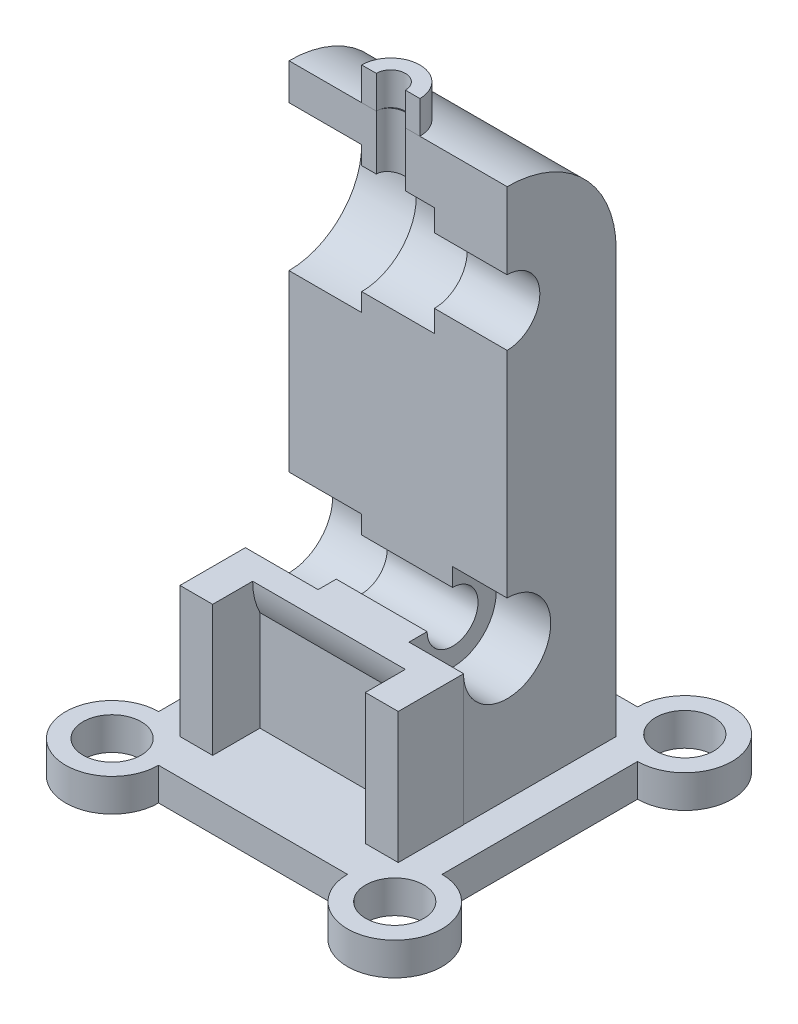
SolidWorks part; units mm, degrees
ref_plane "Ön Düzlem" through (0, 0, 0) normal (0, 0, 1) x (1, 0, 0)
ref_plane "Üst Düzlem" through (0, 0, 0) normal (0, 1, 0) x (1, 0, 0)
ref_plane "Sağ Düzlem" through (0, 0, 0) normal (1, 0, 0) x (0, 0, -1)
sketch "Sketch1" plane through (0, 0, 0) normal (0, 1, 0) x (1, 0, 0)
  line L1 (-62.3416, 5.3221) -> (-10.5841, 5.3221)
  line L2 (-75.3416, -7.6779) -> (-75.3416, -61.6779)
  line L3 (-62.5552, -74.4643) -> (-10.5841, -74.4643)
  line L4 (2.4159, -7.6779) -> (2.4159, -61.4643)
  circle A0 centre (2.4159, 5.3221) radius 8
  circle A1 centre (-75.3416, 5.3221) radius 8
  arc A2 (-62.3416, 5.3221) -> (-75.3416, -7.6779) centre (-75.3416, 5.3221) ccw
  arc A3 (2.4159, -7.6779) -> (-10.5841, 5.3221) centre (2.4159, 5.3221) ccw
  circle A4 centre (-75.3416, -74.4643) radius 8
  arc A5 (-75.3416, -61.6779) -> (-62.5552, -74.4643) centre (-75.3416, -74.4643) ccw
  circle A6 centre (2.4159, -74.4643) radius 8
  arc A7 (-10.5841, -74.4643) -> (2.4159, -61.4643) centre (2.4159, -74.4643) ccw
extrude "Boss-Extrude1" add sketch "Sketch1" along normal blind 9
sketch "Sketch2" plane through (0, 9, 0) normal (0, 1, 0) x (1, 0, 0)
  line L0 (-66.4629, -64.6779) -> (-57.4629, -64.6779)
  line L1 (-66.4629, -4.6779) -> (-6.4629, -4.6779)
  line L2 (-66.4629, -4.6779) -> (-66.4629, -64.6779)
  line L3 (-66.4629, -64.6779) -> (-57.4629, -64.6779)
  line L4 (-6.4629, -4.6779) -> (-6.4629, -64.6779)
  line L5 (-66.4629, -4.6779) -> (-6.4629, -64.6779) construction
  line L6 (-66.4629, -64.6779) -> (-6.4629, -4.6779) construction
  line L8 (-15.4629, -64.6779) -> (-15.4629, -53.6779)
  line L9 (-15.4629, -53.6779) -> (-57.4629, -53.6779)
  line L10 (-57.4629, -53.6779) -> (-57.4629, -64.6779)
  line L11 (-66.4629, -64.6779) -> (-66.4629, -46.6779)
  line L12 (-66.4629, -46.6779) -> (-46.4629, -46.6779)
  line L13 (-46.4629, -46.6779) -> (-46.4629, -41.6779)
  line L14 (-46.4629, -41.6779) -> (-21.4629, -41.6779)
  line L15 (-21.4629, -41.6779) -> (-21.4629, -46.6779)
  line L16 (-21.4629, -46.6779) -> (-6.4629, -46.6779)
  line L17 (-15.4629, -64.6779) -> (-6.4629, -64.6779)
  point P0 (-36.4629, -34.6779)
extrude "Boss-Extrude2" add sketch "Sketch2" along normal blind 36 contours L15 L16 L4 L1 L2 L12 L13 L14
sketch "Sketch3" plane through (-66.4629, 0, 0) normal (-1, 0, 0) x (0, 0, 1)
  line L1 (4.6779, 45) -> (46.6779, 45) construction
  line L2 (34.6779, 45) -> (34.6779, 125)
  line L3 (34.6779, 125) -> (4.6779, 125)
  line L4 (4.6779, 125) -> (4.6779, 45)
  line L5 (4.6779, 45) -> (34.6779, 45)
extrude "Boss-Extrude3" add sketch "Sketch3" against normal blind 60
sketch "Sketch4" plane through (-66.4629, 0, 0) normal (-1, 0, 0) x (0, 0, 1)
  circle A0 centre (34.6779, 45) radius 12
extrude "Cut-Extrude2" cut sketch "Sketch4" against normal blind 20
sketch "Sketch5" plane through (-46.4629, 0, 0) normal (-1, 0, 0) x (0, 0, 1)
  circle A0 centre (34.6779, 45) radius 7
extrude "Cut-Extrude3" cut sketch "Sketch5" against normal blind 25
sketch "Sketch6" plane through (-6.4629, 0, 0) normal (1, 0, 0) x (0, 0, -1)
  circle A0 centre (-34.6779, 45) radius 12
extrude "Cut-Extrude4" cut sketch "Sketch6" against normal blind 15
sketch "Sketch7" plane through (0, 9, 0) normal (0, 1, 0) x (1, 0, 0)
  line L0 (-66.4629, -64.6779) -> (-57.4629, -64.6779)
  line L2 (-66.4629, -46.6779) -> (-66.4629, -64.6779)
  line L3 (-66.4629, -64.6779) -> (-57.4629, -64.6779)
  line L4 (-6.413, -46.6779) -> (-6.413, -64.6779)
  line L5 (-57.4629, -64.6779) -> (-57.4629, -51.6779)
  line L6 (-57.4629, -51.6779) -> (-15.4629, -51.6779)
  line L7 (-15.4629, -51.6779) -> (-15.4629, -64.6779)
  line L8 (-15.4629, -64.6779) -> (-6.413, -64.6779)
  line L9 (-6.413, -46.6779) -> (-21.4629, -46.6779)
  line L10 (-21.4629, -46.6779) -> (-21.4629, -41.6779)
  line L11 (-21.4629, -41.6779) -> (-46.4629, -41.6779)
  line L12 (-46.4629, -41.6779) -> (-46.4629, -46.6779)
  line L13 (-46.4629, -46.6779) -> (-66.4629, -46.6779)
extrude "Boss-Extrude4" add sketch "Sketch7" along normal blind 36
sketch "Sketch9" plane through (-66.4629, 0, 0) normal (-1, 0, 0) x (0, 0, 1)
  line L0 (53.6779, 45) -> (46.6779, 45)
  line L1 (22.6779, 45) -> (15.6779, 45)
  circle A0 centre (34.6779, 125) radius 20
  arc A1 (15.6779, 45) -> (53.6779, 45) centre (34.6779, 45) ccw
  arc A2 (22.6779, 45) -> (46.6779, 45) centre (34.6779, 45) ccw
extrude "Boss-Extrude5" add sketch "Sketch9" against normal blind 60 contours L0 A2 L1 A1
sketch "Sketch10" plane through (-66.4629, 0, 0) normal (-1, 0, 0) x (0, 0, 1)
  circle A0 centre (34.6779, 125) radius 20
extrude "Cut-Extrude5" cut sketch "Sketch10" against normal blind 60
sketch "Sketch11" plane through (-66.4629, 0, 0) normal (-1, 0, 0) x (0, 0, 1)
  line L0 (34.6779, 95) -> (34.6779, 105)
  line L1 (34.6779, 145) -> (34.6779, 155)
  arc A0 (34.6779, 155) -> (34.6779, 95) centre (34.6779, 125) ccw
  arc A1 (34.6779, 145) -> (34.6779, 105) centre (34.6779, 125) ccw
extrude "Boss-Extrude7" add sketch "Sketch11" against normal blind 60
sketch "Sketch13" plane through (0, 0, 34.6779) normal (0, 0, 1) x (1, 0, 0)
  line L0 (-66.4629, 105) -> (-46.4629, 105)
  line L1 (-66.4629, 105) -> (-6.4629, 105) construction
  line L2 (-46.4629, 105) -> (-26.4629, 105)
  line L3 (-26.4629, 105) -> (-6.4629, 105)
  line L4 (-46.4629, 105) -> (-46.4629, 110)
  line L5 (-46.4629, 110) -> (-26.4629, 110)
  line L6 (-26.4629, 110) -> (-26.4629, 116)
  line L7 (-26.4629, 116) -> (-6.4629, 116)
  line L8 (-6.4629, 116) -> (-6.4629, 105)
ref_plane "Plane1" through (-46.4629, 0, 0) normal (-1, 0, 0) x (0, 0, 1)
ref_plane "Plane2" through (-26.4629, 0, 0) normal (-1, 0, 0) x (0, 0, 1)
sketch "Sketch15" plane through (-46.4629, 0, 0) normal (-1, 0, 0) x (0, 0, 1)
  circle A0 centre (34.6779, 125) radius 15
sketch "Sketch16" plane through (-26.4629, 0, 0) normal (-1, 0, 0) x (0, 0, 1)
  circle A0 centre (34.6779, 125) radius 9
sketch "Sketch17" plane through (-46.4629, 0, 0) normal (-1, 0, 0) x (0, 0, 1)
  line L0 (34.6779, 145) -> (34.6779, 140)
  line L1 (34.6779, 110) -> (34.6779, 105)
  circle A0 centre (34.6779, 125) radius 15 construction
  arc A1 (34.6779, 145) -> (34.6779, 105) centre (34.6779, 125) ccw
  arc A2 (34.6779, 140) -> (34.6779, 110) centre (34.6779, 125) ccw
extrude "Boss-Extrude8" add sketch "Sketch17" against normal blind 40
sketch "Sketch18" plane through (-26.4629, 0, 0) normal (-1, 0, 0) x (0, 0, 1)
  line L0 (34.6779, 134) -> (34.6779, 140)
  line L1 (34.6779, 116) -> (34.6779, 110)
  arc A0 (34.6779, 140) -> (34.6779, 110) centre (34.6779, 125) ccw
  arc A1 (34.6779, 134) -> (34.6779, 116) centre (34.6779, 125) ccw
extrude "Boss-Extrude9" add sketch "Sketch18" against normal blind 20
ref_plane "Plane3" through (0, 155, 0) normal (0, 1, 0) x (1, 0, 0)
sketch "Sketch19" plane through (0, 155, 0) normal (0, 1, 0) x (1, 0, 0)
  line L0 (-66.4629, -34.6779) -> (-38.4629, -34.6779)
  line L1 (-66.4629, -4.6779) -> (-66.4629, -64.6779) construction
  line L2 (-6.4629, -34.6779) -> (-66.4629, -34.6779) construction
  line L3 (-46.4629, -34.6779) -> (-30.4629, -34.6779)
  arc A0 (-30.4629, -34.6779) -> (-46.4629, -34.6779) centre (-38.4629, -34.6779) ccw
  arc A1 (-34.4629, -34.6779) -> (-42.4629, -34.6779) centre (-38.4629, -34.6779) ccw
extrude "Boss-Extrude10" add sketch "Sketch19" along normal blind 9 separate body contours A1 L3 A0 L0
sketch "Sketch20" plane through (0, 155, 0) normal (0, 1, 0) x (1, 0, 0)
  circle A0 centre (-38.4629, -34.6779) radius 4
extrude "Cut-Extrude6" cut sketch "Sketch20" against normal blind 18
